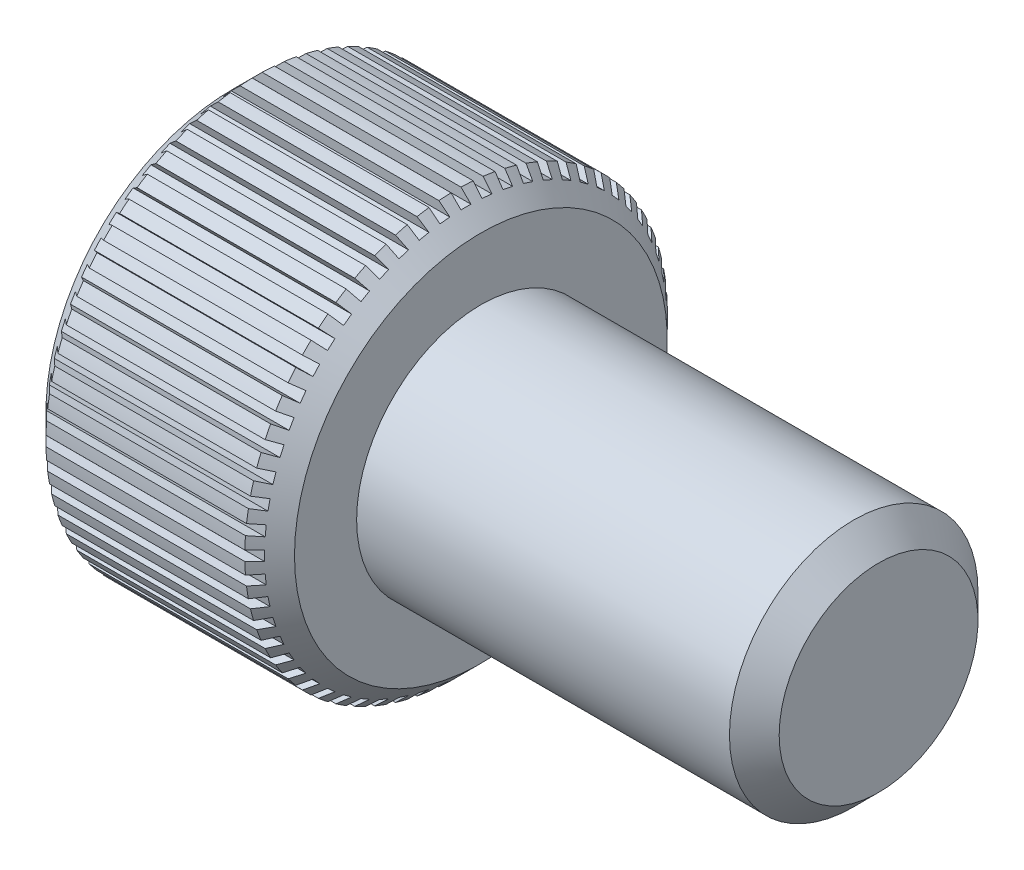
SolidWorks part; units mm, degrees
ref_plane "Front Plane" through (0, 0, 0) normal (0, 0, 1) x (1, 0, 0)
ref_plane "Top Plane" through (0, 0, 0) normal (0, 1, 0) x (1, 0, 0)
ref_plane "Right Plane" through (0, 0, 0) normal (1, 0, 0) x (0, 0, -1)
sketch "Sketch1" plane through (0, 0, 0) normal (0, 0, 1) x (1, 0, 0)
  line L0 (0, 0) -> (13, 0) construction
  line L1 (13, 0) -> (13, 2.5)
  line L2 (13, 2.5) -> (5, 2.5)
  line L3 (5, 2.5) -> (5, 4.25)
  line L4 (5, 4.25) -> (0, 4.25)
  line L5 (0, 4.25) -> (0, 0)
  line L6 (0, 0) -> (13, 0)
  dimension "D1" = 5
  dimension "D2" = 8.5
  dimension "D3" = 8
  dimension "D4" = 5
revolve "Revolve1" add sketch "Sketch1" angle 360 about L0
cosmetic thread "Cosmetic Thread1" parameters "D2"=4
chamfer "Chamfer1" distance 0.5 angle 45 3 edges at (13, 0, 2.5) (5, 0, 4.25) (0, 0, 4.25)
sketch "Sketch2" plane through (0, 0, 0) normal (-1, 0, 0) x (0, 0, 1)
  line L0 (-3.75, 0) -> (-4.25, 0) construction
  line L1 (-4.25, 0.1) -> (-4.05, 0.1)
  line L2 (-4.25, -0.1) -> (-4.05, -0.1)
  line L3 (0, 0) -> (-3.75, 0) construction
  line L4 (-4.25, 0.1) -> (-4.25, -0.1)
  line L5 (-4.05, 0.1) -> (-4.05, -0.1)
  circle A0 centre (0, 0) radius 3.75 construction
  circle A1 centre (0, 0) radius 4.25 construction
  point P1 (-3.75, 0.1)
  point P16 (-4, 0)
  dimension "D1" = 0.2
  dimension "D2" = 0.2
extrude "Cut-Extrude1" cut sketch "Sketch2" against normal through all
pattern_circular "CirPattern1" count 60 over 360 about axis through (0, 0, 0) along (1, 0, 0) of "Cut-Extrude1"
sketch "Sketch3" plane through (0, 0, 0) normal (-1, 0, 0) x (0, 0, 1)
  line L1 (-1.7321, 0) -> (-0.866, -1.5)
  line L2 (-0.866, -1.5) -> (0.866, -1.5)
  line L3 (0.866, -1.5) -> (1.7321, 0)
  line L4 (1.7321, 0) -> (0.866, 1.5)
  line L5 (0.866, 1.5) -> (-0.866, 1.5)
  line L6 (-0.866, 1.5) -> (-1.7321, 0)
  circle A0 centre (0, 0) radius 1.5 construction
  dimension "D1" = 3
extrude "Cut-Extrude2" cut sketch "Sketch3" against normal blind 2.5
equation "\"a\"= 1"
equation "\"b\"= 1"
equation "\"c\"= 1"
equation "\"d\"= 1"
equation "\"e\"= 1"
equation "\"x\"= 1"
equation "\"y\"= 1"
equation "\"z\"= 1"
